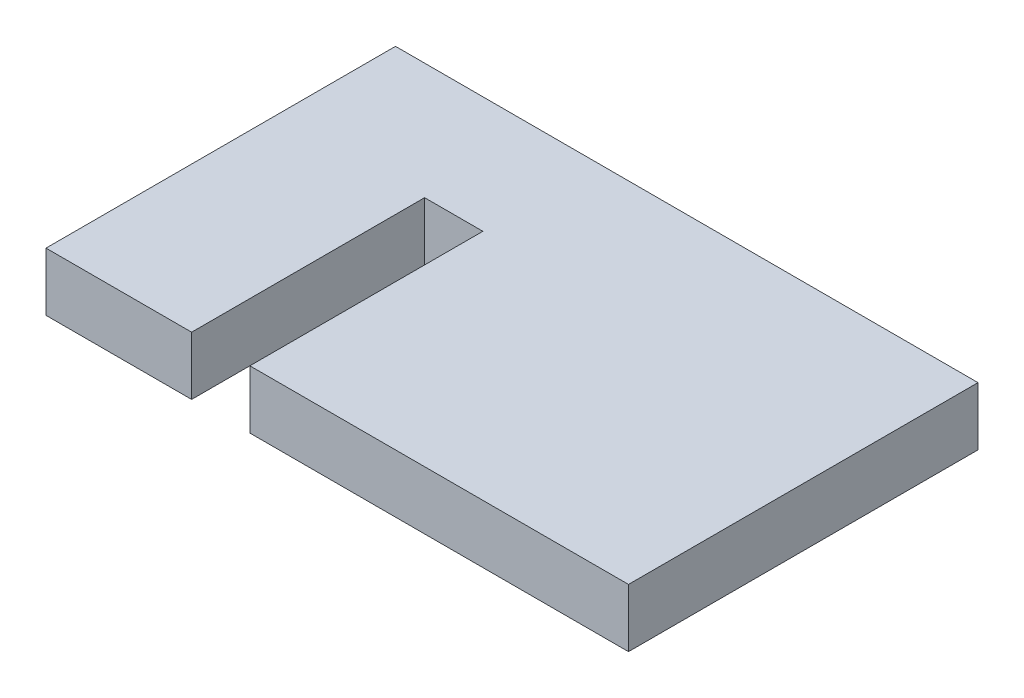
SolidWorks part; units mm, degrees
ref_plane "Front Plane" through (0, 0, 0) normal (0, 0, 1) x (1, 0, 0)
ref_plane "Top Plane" through (0, 0, 0) normal (0, 1, 0) x (1, 0, 0)
ref_plane "Right Plane" through (0, 0, 0) normal (1, 0, 0) x (0, 0, -1)
sketch "Sketch2" plane through (0, 0, 0) normal (0, 1, 0) x (1, 0, 0)
  line L1 (0, 0) -> (63.5, 0)
  line L2 (0, 0) -> (0, 38.1)
  line L3 (0, 38.1) -> (63.5, 38.1)
  line L4 (63.5, 0) -> (63.5, 38.1)
  dimension "D1" = 63.5
  dimension "D2" = 38.1
extrude "Boss-Extrude1" add sketch "Sketch2" along normal blind 6.35
sketch "Sketch3" plane through (0, 0, 0) normal (0, -1, 0) x (1, 0, 0)
  line L0 (0, 0) -> (63.5, 0) construction
  line L1 (15.875, 0) -> (22.225, 0)
  line L2 (15.875, 0) -> (15.875, -25.4)
  line L3 (15.875, -25.4) -> (22.225, -25.4)
  line L4 (22.225, 0) -> (22.225, -25.4)
  line L5 (0, -38.1) -> (0, 0) construction
  dimension "D1" = 25.4
  dimension "D2" = 15.875
  dimension "D3" = 6.35
extrude "Cut-Extrude1" cut sketch "Sketch3" against normal through all
equation "\"support_thickness\"= 0.25"
equation "\"support_height\"= 1.5"
equation "\"support_width\"=1.5"
equation "\"D1@Sketch2\"=\"support_width\"+1"
equation "\"D2@Sketch2\"=\"support_height\""
equation "\"D1@Boss-Extrude1\"=\"support_thickness\""
equation "\"D1@Sketch3\"=\"support_height\"-0.5"
equation "\"D2@Sketch3\"=(\"support_width\"-\"support_thickness\")/2"
equation "\"D3@Sketch3\"=\"support_thickness\""
